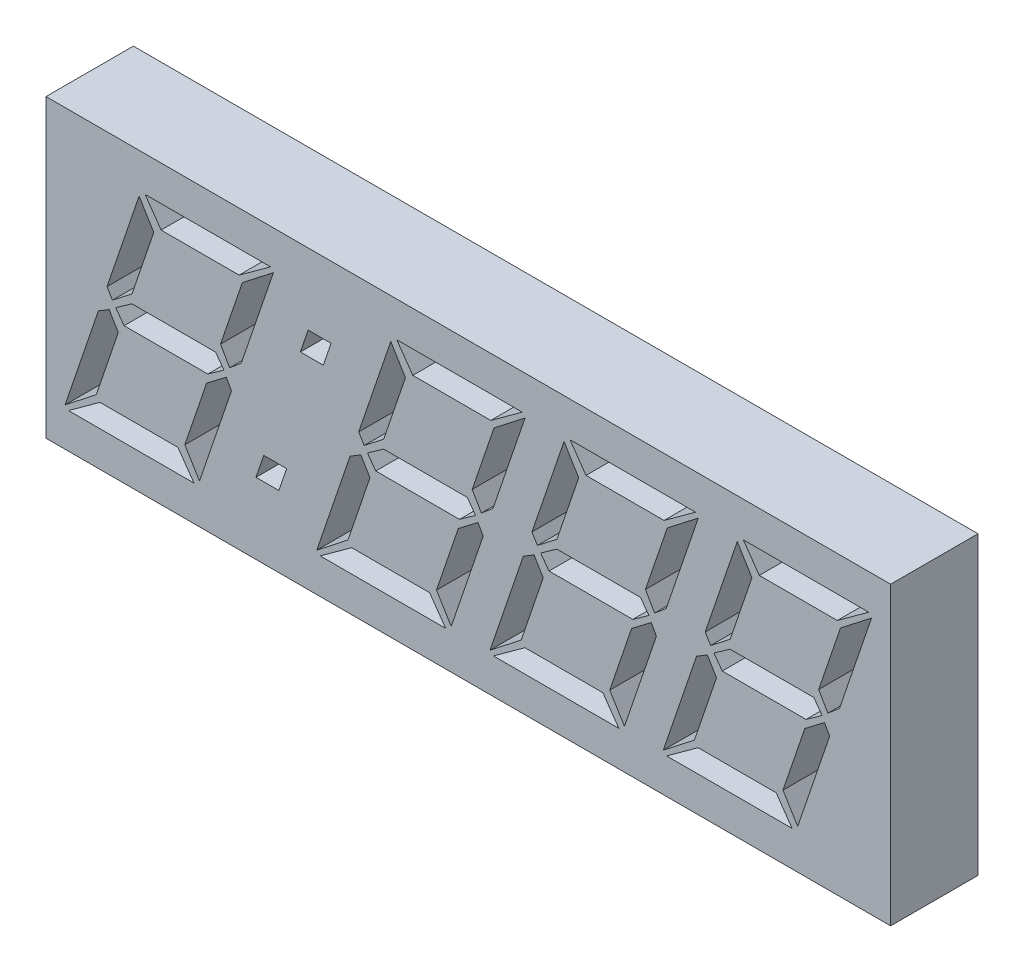
SolidWorks part; units mm, degrees
ref_plane "Спереди" through (0, 0, 0) normal (0, 0, 1) x (1, 0, 0)
ref_plane "Сверху" through (0, 0, 0) normal (0, 1, 0) x (1, 0, 0)
ref_plane "Справа" through (0, 0, 0) normal (1, 0, 0) x (0, 0, -1)
sketch "Эскиз1" plane through (0, 0, 0) normal (0, 0, 1) x (1, 0, 0)
  line L9 (65.1785, -93.2379) -> (565.1785, -93.2379)
  line L10 (65.1785, -93.2379) -> (65.1785, -313.2379)
  line L11 (65.1785, -313.2379) -> (565.1785, -313.2379)
  line L12 (565.1785, -93.2379) -> (565.1785, -313.2379)
  text T0 "<i>8:888</i>" font "DS-Digital" height 130
  dimension "D1" = 500
  dimension "D2" = 220
extrude "Бобышка-Вытянуть1" add sketch "Эскиз1" along normal blind 50
sketch "Эскиз2" plane through (0, 0, 50) normal (0, 0, 1) x (1, 0, 0)
  line L0 (225.057, -151.9154) -> (238.1505, -151.9154)
  line L1 (238.1505, -151.9154) -> (233.6789, -165.009)
  line L2 (233.6789, -165.009) -> (220.5853, -165.009)
  line L3 (220.5853, -165.009) -> (225.057, -151.9154)
  line L4 (199.6439, -226.7311) -> (212.7374, -226.7311)
  line L5 (212.7374, -226.7311) -> (208.2658, -239.8246)
  line L6 (208.2658, -239.8246) -> (195.1722, -239.8246)
  line L7 (195.1722, -239.8246) -> (199.6439, -226.7311)
  line L8 (303.7058, -260.4046) -> (231.896, -260.4046) construction
  dimension "D1" = 20.58
  dimension "D2" = 13.0935
  dimension "D3" = 13.836
  dimension "D4" = 0
extrude "Вырез-Вытянуть1" cut sketch "Эскиз2" against normal blind 65
sketch "Эскиз3" plane through (0, 0, 50) normal (0, 0, 1) x (1, 0, 0)
  line L1 (183.9606, -243.9126) -> (208.9541, -243.9126)
  line L2 (183.9606, -243.9126) -> (183.9606, -268.6669)
  line L3 (183.9606, -268.6669) -> (208.9541, -268.6669)
  line L4 (208.9541, -243.9126) -> (208.9541, -268.6669)
extrude "Бобышка-Вытянуть2" add sketch "Эскиз3" against normal blind 50
sketch "Эскиз4" plane through (0, 0, 50) normal (0, 0, 1) x (1, 0, 0)
  line L0 (131.7364, -131.3399) -> (203.5462, -131.3399) construction
  line L1 (67.9383, -94.3399) -> (565.4266, -94.3399)
  line L2 (67.9383, -94.3399) -> (67.9383, -297.4046)
  line L3 (67.9383, -297.4046) -> (565.4266, -297.4046)
  line L4 (565.4266, -94.3399) -> (565.4266, -297.4046)
  line L5 (159.6771, -260.4046) -> (87.8673, -260.4046) construction
  dimension "D1" = 37
  dimension "D2" = 37
  dimension "D3" = 18
  dimension "D4" = 18
extrude "Вырез-Вытянуть-Тонкостенный1" cut sketch "Эскиз4" against normal blind 84 thin thin type one direction wall 30
scale "Масштаб1" scale about centroid uniform scaling yes scale factor 1.5
sketch "Эскиз8" plane through (0, 0, 62.5) normal (0, 0, 1) x (1, 0, 0)
  line L0 (82.3709, -292.676) -> (-25.3438, -292.676) construction
  line L1 (-43.2372, -69.0789) -> (678.9952, -69.0789)
  line L2 (-43.2372, -69.0789) -> (-43.2372, -322.676)
  line L3 (-43.2372, -322.676) -> (678.9952, -322.676)
  line L4 (678.9952, -69.0789) -> (678.9952, -322.676)
  line L5 (40.46, -99.0789) -> (148.1747, -99.0789) construction
  dimension "D1" = 15
  dimension "D2" = 15
  dimension "D3" = 30
  dimension "D4" = 30
extrude "Вырез-Вытянуть-Тонкостенный2" cut sketch "Эскиз8" against normal blind 180 thin thin type one direction wall 50
sketch "Эскиз9" plane through (0, 0, 62.5) normal (0, 0, 1) x (1, 0, 0)
  line L1 (-44.6222, -68.8789) -> (680.3778, -68.8789)
  line L2 (-44.6222, -68.8789) -> (-44.6222, -322.8789)
  line L3 (-44.6222, -322.8789) -> (680.3778, -322.8789)
  line L4 (680.3778, -68.8789) -> (680.3778, -322.8789)
  line L5 (-43.2372, -69.0789) -> (-43.2372, -322.676) construction
  line L6 (678.9952, -69.0789) -> (-43.2372, -69.0789) construction
  line L8 (-36.8745, -75.9587) -> (671.3746, -75.9587)
  line L9 (-36.8745, -75.9587) -> (-36.8745, -316.8536)
  line L10 (-36.8745, -316.8536) -> (671.3746, -316.8536)
  line L11 (671.3746, -75.9587) -> (671.3746, -316.8536)
  dimension "D1" = 725
  dimension "D2" = 254
  dimension "D3" = 1.385
  dimension "D4" = 0.2
extrude "Бобышка-Вытянуть4" add sketch "Эскиз9" against normal blind 75
